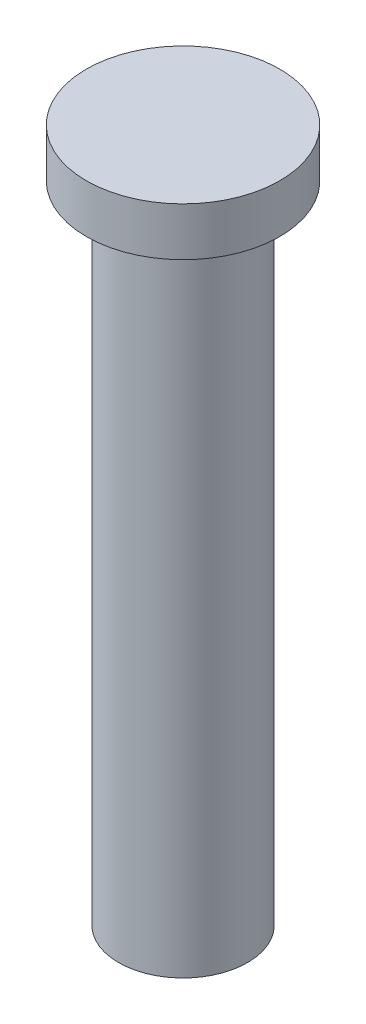
SolidWorks part; units mm, degrees
ref_plane "前视基准面" through (0, 0, 0) normal (0, 0, 1) x (1, 0, 0)
ref_plane "上视基准面" through (0, 0, 0) normal (0, 1, 0) x (1, 0, 0)
ref_plane "右视基准面" through (0, 0, 0) normal (1, 0, 0) x (0, 0, -1)
other "Configuration Table"
sketch "草图1" plane through (0, 0, 0) normal (0, 1, 0) x (1, 0, 0)
  circle A0 centre (0, 0) radius 2
  dimension "D1" = 4
extrude "凸台-拉伸1" add sketch "草图1" along normal blind 20
sketch "草图2" plane through (0, 20, 0) normal (0, 1, 0) x (1, 0, 0)
  circle A0 centre (0, 0) radius 3
  dimension "D1" = 6
extrude "凸台-拉伸2" add sketch "草图2" along normal blind 1.5
